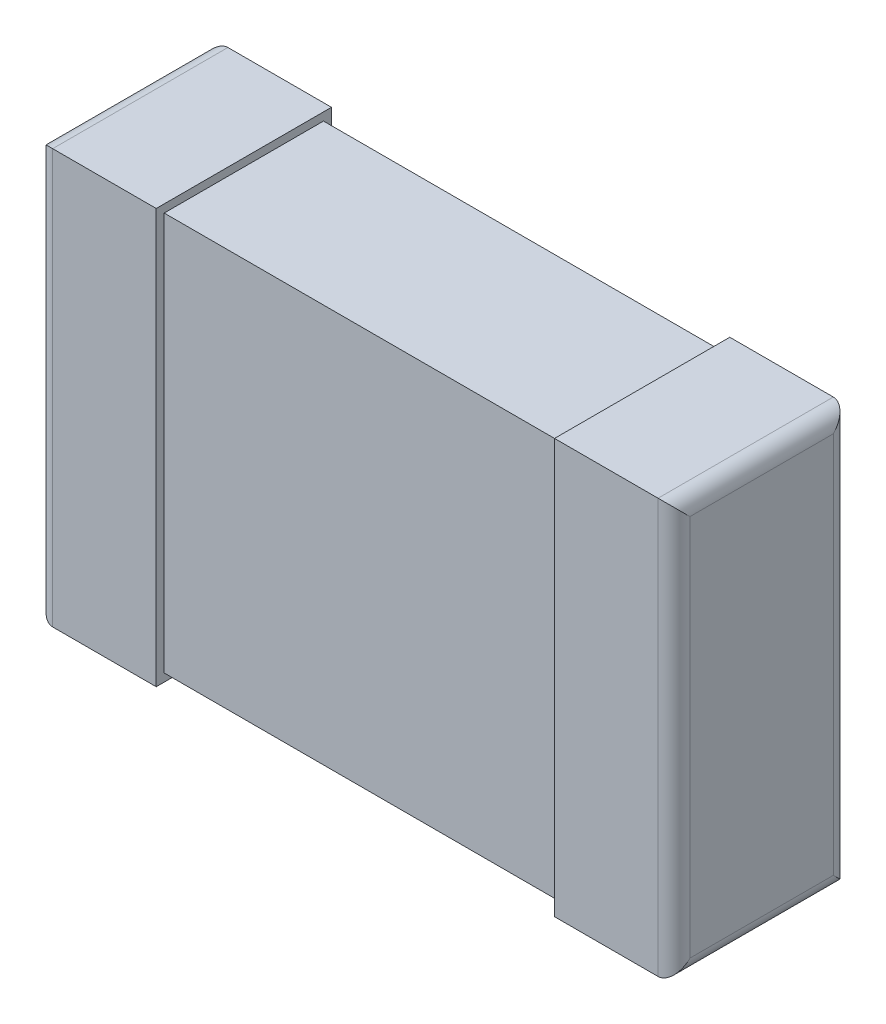
SolidWorks part; units mm, degrees
ref_plane "Front Plane" through (0, 0, 0) normal (0, 0, 1) x (1, 0, 0)
ref_plane "Top Plane" through (0, 0, 0) normal (0, 1, 0) x (1, 0, 0)
ref_plane "Right Plane" through (0, 0, 0) normal (1, 0, 0) x (0, 0, -1)
sketch "Sketch1" plane through (0, 0, 0) normal (0, 0, 1) x (1, 0, 0)
  line L1 (0, 0) -> (2.032, 0)
  line L2 (0, 0) -> (0, 1.27)
  line L3 (0, 1.27) -> (2.032, 1.27)
  line L4 (2.032, 0) -> (2.032, 1.27)
  dimension "D1" = 1.27
  dimension "D2" = 2.032
extrude "Boss-Extrude1" add sketch "Sketch1" along normal blind 0.508
sketch "Sketch2" plane through (0, 0, 0) normal (-1, 0, 0) x (0, 0, 1)
  line L8 (-0.0254, 1.2954) -> (-0.0254, -0.0254)
  line L9 (-0.0254, -0.0254) -> (0.5334, -0.0254)
  line L10 (0.5334, -0.0254) -> (0.5334, 1.2954)
  line L11 (0.5334, 1.2954) -> (-0.0254, 1.2954)
  line L12 (-0.0254, 1.2954) -> (-0.0254, -0.0254)
  line L13 (-0.0254, -0.0254) -> (0.5334, -0.0254)
  line L14 (0.5334, -0.0254) -> (0.5334, 1.2954)
  line L15 (0.5334, 1.2954) -> (-0.0254, 1.2954)
  dimension "D1" = 0.0254
extrude "Boss-Extrude2" add sketch "Sketch2" against normal blind 0.381
ref_plane "Plane1" through (1.016, 0, 0) normal (-1, 0, 0) x (0, 0, 1)
mirror "Mirror1" about plane through (1.016, 0, 0) normal (-1, 0, 0) of "Boss-Extrude2"
fillet "Fillet1" radius 0.0508 8 edges at (2.032, 0.635, -0.0254) (2.032, -0.0254, 0.254) (2.032, 0.635, 0.5334) (2.032, 1.2954, 0.254) (0, 0.635, 0.5334) (0, -0.0254, 0.254) (0, 0.635, -0.0254) (0, 1.2954, 0.254)
